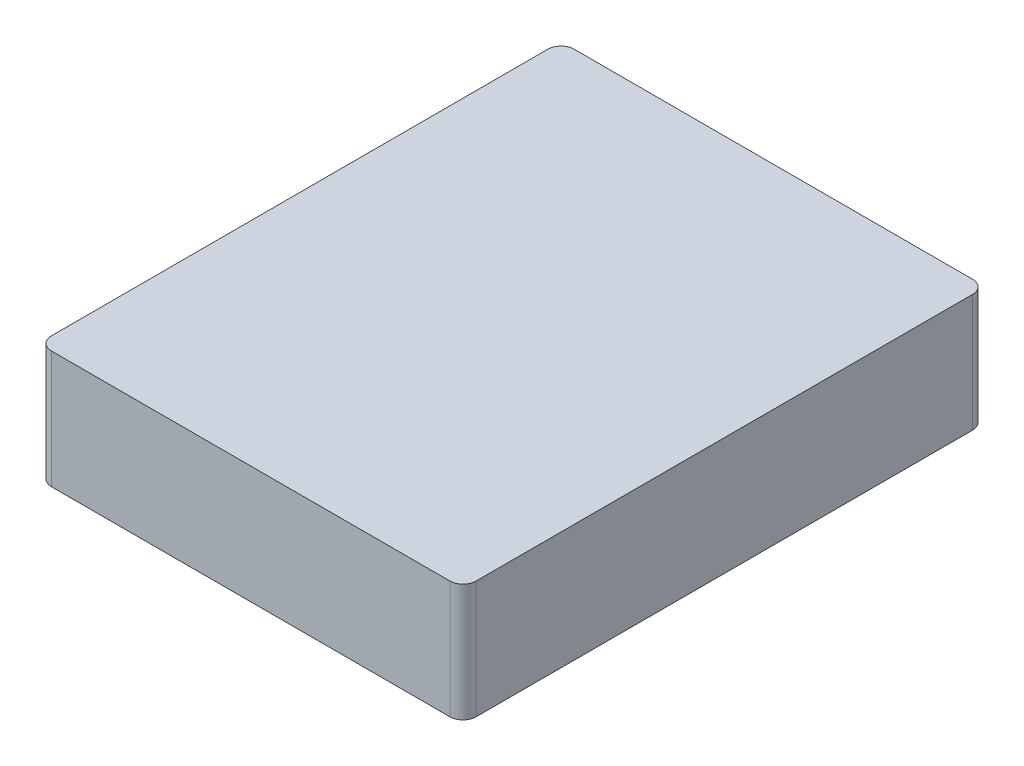
SolidWorks part; units mm, degrees
ref_plane "Front Plane" through (0, 0, 0) normal (0, 0, 1) x (1, 0, 0)
ref_plane "Top Plane" through (0, 0, 0) normal (0, 1, 0) x (1, 0, 0)
ref_plane "Right Plane" through (0, 0, 0) normal (1, 0, 0) x (0, 0, -1)
sketch "Sketch1" plane through (0, 0, 0) normal (0, 1, 0) x (1, 0, 0)
  line L1 (-32.5, -40) -> (32.5, -40)
  line L2 (-32.5, -40) -> (-32.5, 40)
  line L3 (-32.5, 40) -> (32.5, 40)
  line L4 (32.5, -40) -> (32.5, 40)
  line L5 (-32.5, -40) -> (32.5, 40) construction
  line L6 (-32.5, 40) -> (32.5, -40) construction
  point P0 (0, 0)
extrude "Boss-Extrude1" add sketch "Sketch1" along normal blind 18
fillet "Fillet1" radius 2 4 edges at (-32.5, 9, -40) (32.5, 9, -40) (32.5, 9, 40) (-32.5, 9, 40)
